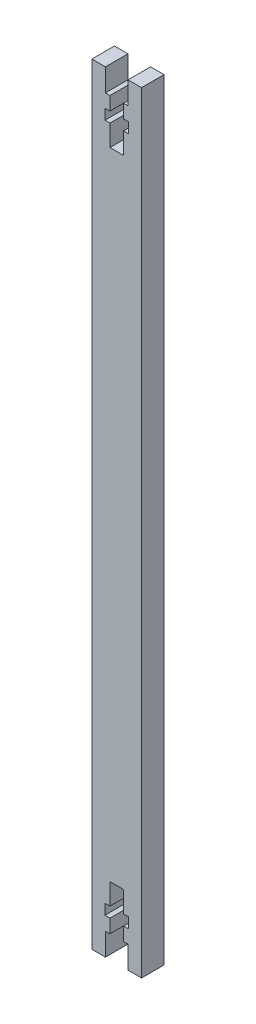
SolidWorks part; units mm, degrees
ref_plane "Front Plane" through (0, 0, 0) normal (0, 0, 1) x (1, 0, 0)
ref_plane "Top Plane" through (0, 0, 0) normal (0, 1, 0) x (1, 0, 0)
ref_plane "Right Plane" through (0, 0, 0) normal (1, 0, 0) x (0, 0, -1)
sketch "Sketch1" plane through (0, 0, 0) normal (0, 0, 1) x (1, 0, 0)
  line L0 (-9, 166) -> (-9, 5)
  line L5 (-20, 166) -> (-20, 5)
  line L6 (-14.5, 5) -> (-14.5, 16.2208) construction
  line L7 (-16, 5) -> (-17, 5)
  line L8 (-17, 0) -> (-20, 0)
  line L9 (-20, 0) -> (-20, 5)
  line L10 (-17, 0) -> (-17, 5)
  line L11 (-13, 5) -> (-12, 5)
  line L12 (-12, 5) -> (-12, 0)
  line L13 (-12, 0) -> (-9, 0)
  line L14 (-9, 0) -> (-9, 5)
  line L15 (-14.5, 166) -> (-14.5, 94.1792) construction
  line L16 (-13, 166) -> (-12, 166)
  line L17 (-12, 171) -> (-9, 171)
  line L18 (-9, 171) -> (-9, 166)
  line L19 (-12, 171) -> (-12, 166)
  line L20 (-16, 166) -> (-17, 166)
  line L21 (-17, 166) -> (-17, 171)
  line L22 (-17, 171) -> (-20, 171)
  line L23 (-20, 171) -> (-20, 166)
  line L24 (-13, 166) -> (-16, 166) construction
  line L25 (-16, 166) -> (-16, 163)
  line L26 (-16, 160.7) -> (-17.1, 160.7)
  line L27 (-11.9, 163) -> (-11.9, 160.7)
  line L28 (-17.1, 163) -> (-16, 163)
  line L29 (-16, 160.7) -> (-16, 156)
  line L30 (-16, 156) -> (-13, 156)
  line L31 (-13, 156) -> (-13, 160.7)
  line L32 (-13, 163) -> (-11.9, 163)
  line L33 (-17.1, 160.7) -> (-17.1, 163)
  line L34 (-11.9, 160.7) -> (-13, 160.7)
  line L35 (-13, 163) -> (-13, 166)
  line L36 (-14.5, 156) -> (-14.5, 166) construction
  line L37 (-16, 5) -> (-13, 5) construction
  line L38 (-13, 5) -> (-13, 8)
  line L39 (-13, 10.3) -> (-11.9, 10.3)
  line L40 (-17.1, 8) -> (-17.1, 10.3)
  line L41 (-11.9, 8) -> (-13, 8)
  line L42 (-13, 10.3) -> (-13, 15)
  line L43 (-13, 15) -> (-16, 15)
  line L44 (-16, 15) -> (-16, 10.3)
  line L45 (-16, 8) -> (-17.1, 8)
  line L46 (-11.9, 10.3) -> (-11.9, 8)
  line L47 (-17.1, 10.3) -> (-16, 10.3)
  line L48 (-16, 8) -> (-16, 5)
  line L49 (-14.5, 15) -> (-14.5, 5) construction
  point P4 (-18.5, 0)
  dimension "D1" = 5
  dimension "D2" = 3
  dimension "D3" = 5
  dimension "D5" = 3
  dimension "D6" = 5
  dimension "D7" = 5.2
  dimension "D8" = 3
  dimension "D9" = 2.3
  dimension "D10" = 3
  dimension "D11" = 10
  dimension "D12" = 5.2
  dimension "D13" = 3
  dimension "D14" = 2.3
  dimension "D15" = 3
  dimension "D16" = 10
  dimension "D17" = 171
extrude "Boss-Extrude1" add sketch "Sketch1" along normal blind 5
sketch "Sketch2" plane through (0, 0, 5) normal (0, 0, 1) x (1, 0, 0)
  line L0 (-18.9476, 274.152) -> (-18.9476, -26.6804) construction
  line L1 (-9, 0) -> (-9, 171) construction
  dimension "D1" = 9.9476
